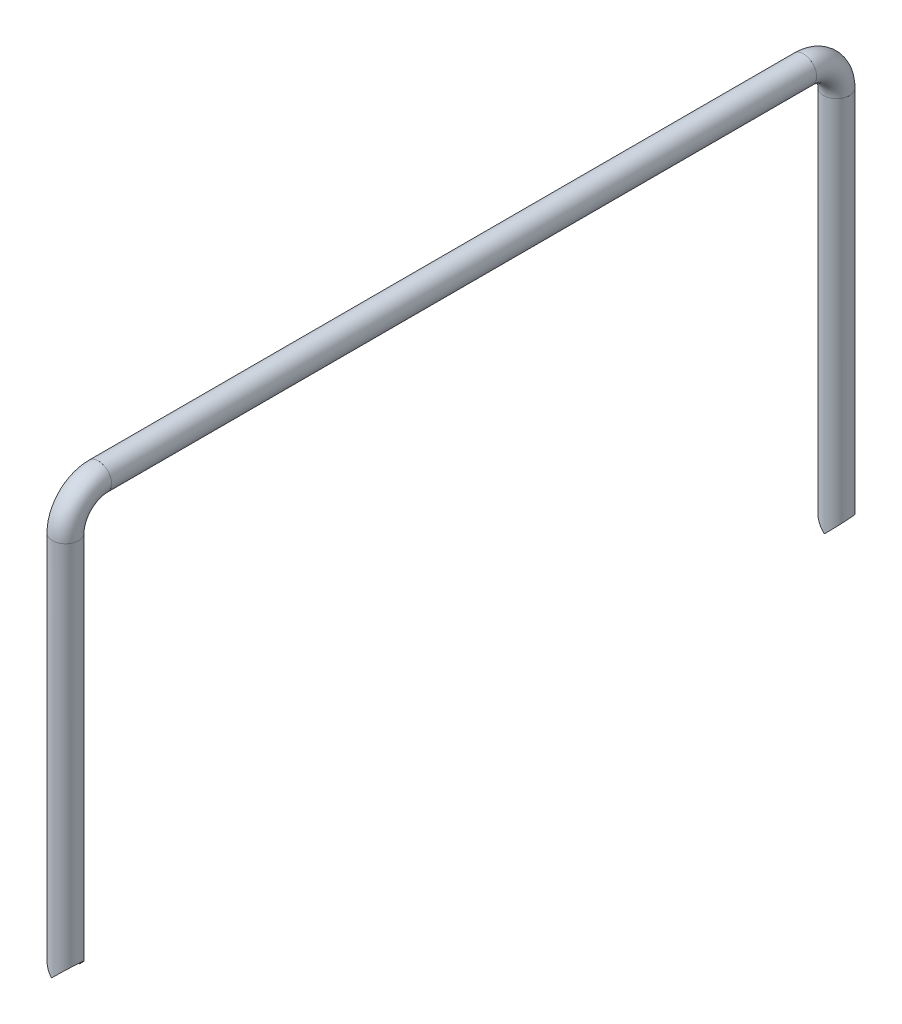
SolidWorks part; units mm, degrees
material "AISI 304"
ref_plane "Plano frontal" through (0, 0, 0) normal (0, 0, 1) x (1, 0, 0)
ref_plane "Plano superior" through (0, 0, 0) normal (0, 1, 0) x (1, 0, 0)
ref_plane "Plano direito" through (0, 0, 0) normal (1, 0, 0) x (0, 0, -1)
ref_plane "Plano1" through (0, 250, 0) normal (0, 1, 0) x (1, 0, 0)
sketch "Esboço1" plane through (0, 0, 0) normal (0, 1, 0) x (1, 0, 0)
  line L0 (0, 162.7552) -> (0, -162.7552)
  line L1 (0, 0) -> (910, 0) construction
  line L2 (910, 265) -> (910, -265) construction
  line L3 (37.1501, 202.6536) -> (910, 265)
  line L4 (37.1501, -202.6536) -> (910, -265)
  arc A0 (0, -162.7552) -> (37.1501, -202.6536) centre (40, -162.7552) ccw
  arc A1 (0, 162.7552) -> (37.1501, 202.6536) centre (40, 162.7552) cw
  point P9 (0, -200)
  point P12 (0, 200)
  dimension "D3" = 40
  dimension "D1" = 400
  dimension "D2" = 910
  dimension "D4" = 530
sketch "Esboço2" plane through (0, 250, 0) normal (0, 1, 0) x (1, 0, 0)
  line L0 (0, 162.7552) -> (0, -162.7552) construction
  line L1 (0, 0) -> (910, 0) construction
  line L2 (910, 265) -> (910, -265) construction
  line L3 (37.1501, 202.6536) -> (910, 265) construction
  line L4 (37.1501, -202.6536) -> (910, -265) construction
  arc A0 (0, -162.7552) -> (37.1501, -202.6536) centre (40, -162.7552) ccw construction
  arc A1 (0, 162.7552) -> (37.1501, 202.6536) centre (40, 162.7552) cw construction
  point P9 (0, -200)
  point P12 (0, 200)
  dimension "D3" = 40
  dimension "D1" = 400
  dimension "D2" = 910
  dimension "D4" = 530
sketch3d "3DSketch1"
  line L0 (37.1501, 0, 202.6536) -> (910, 0, 265) construction
  line L1 (58.5316, 250, 185.1239) -> (58.5316, 250, 204.1808) construction
  line L2 (58.5316, 250, -185.0557) -> (58.5316, 250, -204.1808) construction
  line L4 (58.5316, 250, -184.1808) -> (58.5316, 250, 184.1808)
  line L7 (58.5316, 250, 185.1239) -> (58.5316, 250, -185.0557) construction
  line L8 (58.5316, 230, 204.1808) -> (58.5316, 0, 204.1808)
  line L11 (58.5316, 230, -204.1808) -> (58.5316, 0, -204.1808)
  line L12 (0, 250, -162.7552) -> (0, 250, 162.7552) construction
  line L14 (37.1501, 0, -202.6536) -> (910, 0, -265) construction
  arc A0 (58.5316, 230, -204.1808) -> (58.5316, 250, -184.1808) centre (58.5316, 230, -184.1808) ccw
  arc A1 (58.5316, 230, 204.1808) -> (58.5316, 250, 184.1808) centre (58.5316, 230, 184.1808) ccw
  point P5 (58.5316, 250, -204.1808)
  point P7 (78.5316, 230, -184.1808)
  point P11 (58.5316, 250, 204.1808)
  point P13 (38.5316, 230, 184.1808)
  point P17 (37.1501, 0, -202.6536)
  point P18 (87.0231, 0, -206.2159)
  point P34 (196.7435, 15.88, -214.0531)
  dimension "D2" = 20
  dimension "D13" = 58.5316
sketch "Esboço4" plane through (0, 250, 0) normal (0, 1, 0) x (1, 0, 0)
  line L0 (60.0173, 204.287) -> (60.0173, -204.287) construction
  line L1 (37.1501, 202.6536) -> (910, 265) construction
  line L2 (0, 200) -> (0, -200) construction
  line L3 (0, -200) -> (910, -265) construction
  line L4 (0, 0) -> (910, 0) construction
  line L5 (910, -265) -> (910, 265) construction
  line L6 (910, 265) -> (0, 200) construction
  point P3 (60.0173, 0)
sketch "Esboço6" plane through (0, 0, 0) normal (0, 0, 1) x (1, 0, 0)
  circle A0 centre (0, 0) radius 7.9375
sketch3d "3DSketch2"
  line L0 (473.5751, 0, 233.8268) -> (473.5751, 230, 233.8268)
  line L1 (37.1501, 0, 202.6536) -> (910, 0, 265) construction
  line L2 (37.1501, 250, 202.6536) -> (910, 250, 265) construction
  line L3 (473.5751, 250, 213.8268) -> (473.5751, 250, -213.8268)
  line L4 (37.1501, 250, -202.6536) -> (910, 250, -265) construction
  line L5 (473.5751, 230, -233.8268) -> (473.5751, 0, -233.8268)
  line L6 (37.1501, 0, -202.6536) -> (910, 0, -265) construction
  arc A0 (473.5751, 250, -213.8268) -> (473.5751, 230, -233.8268) centre (473.5751, 230, -213.8268) ccw
  arc A1 (473.5751, 230, 233.8268) -> (473.5751, 250, 213.8268) centre (473.5751, 230, 213.8268) ccw
  point P14 (473.5751, 250, -233.8268)
  point P15 (453.5751, 230, -213.8268)
  point P18 (473.5751, 250, 233.8268)
  point P19 (453.5751, 230, 213.8268)
  dimension "D1" = 20
other "Pipe - configured 21.3 X 2.3(1)"
ref_plane "Plano2" through (473.5751, 0, 233.8268) normal (0, 1, 0) x (1, 0, 0)
sketch "Sketch1" plane through (473.5751, 0, 233.8268) normal (0, 1, 0) x (1, 0, 0)
  circle A0 centre (0, 0) radius 6.4375
  circle A1 centre (0, 0) radius 7.9375
  point P3 (0, 0)
  dimension "Out_dia" = 15.875
  dimension "D1" = 1.5
sweep "Varredura de corte1" cut profiles "Esboço6" path "Esboço1"
